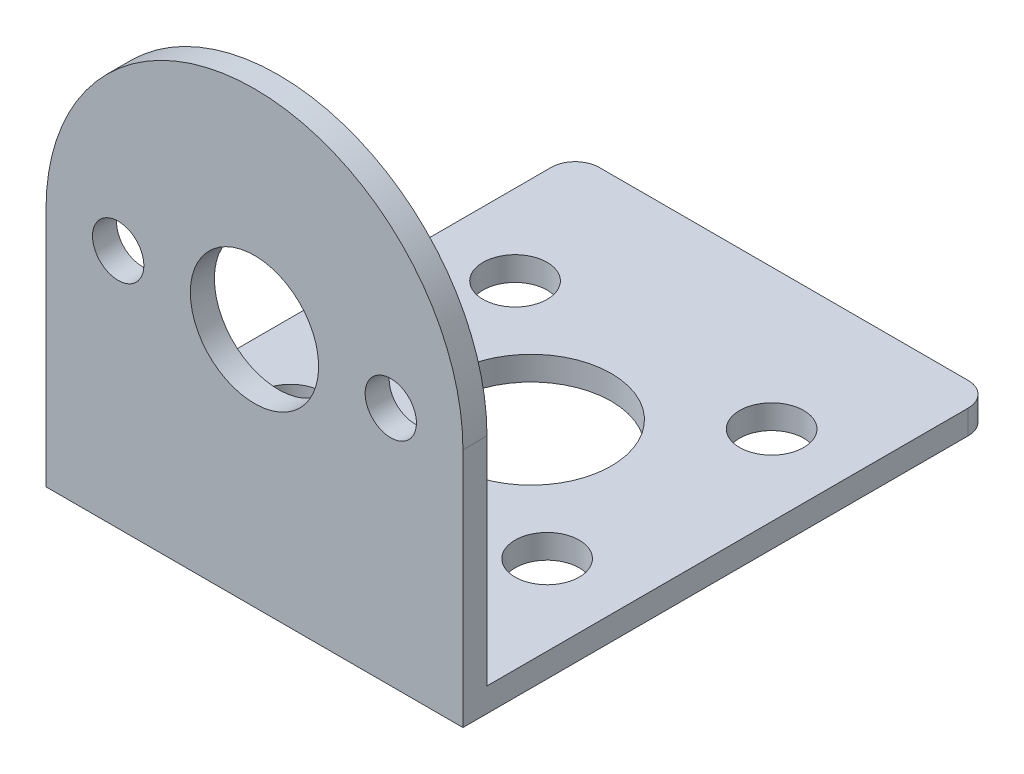
SolidWorks part; units mm, degrees
ref_plane "Front Plane" through (0, 0, 0) normal (0, 0, 1) x (1, 0, 0)
ref_plane "Top Plane" through (0, 0, 0) normal (0, 1, 0) x (1, 0, 0)
ref_plane "Right Plane" through (0, 0, 0) normal (1, 0, 0) x (0, 0, -1)
sketch "Sketch1" plane through (0, 0, 0) normal (0, 0, 1) x (1, 0, 0)
  line L1 (0, 0) -> (26, 0)
  line L2 (0, 0) -> (0, 15)
  line L4 (26, 0) -> (26, 15)
  arc A1 (26, 15) -> (0, 15) centre (13, 15) ccw
extrude "Boss-Extrude1" add sketch "Sketch1" along normal blind 1.5
sketch "Sketch2" plane through (0, 0, 0) normal (0, 0, -1) x (-1, 0, 0)
  circle A0 centre (-21.5, 15) radius 1.6
  circle A1 centre (-13, 15) radius 4
  circle A4 centre (-4.5, 15) radius 1.6
extrude "Cut-Extrude1" cut sketch "Sketch2" against normal through all
sketch "Sketch3" plane through (0, 0, 0) normal (0, 0, -1) x (-1, 0, 0)
  line L0 (0, 15) -> (0, 0) construction
  line L1 (-26, 0) -> (0, 0)
  line L2 (-26, 0) -> (-26, 1.5)
  line L3 (-26, 1.5) -> (0, 1.5)
  line L4 (0, 0) -> (0, 1.5)
extrude "Boss-Extrude4" add sketch "Sketch3" along normal blind 31.5
sketch "Sketch4" plane through (0, 0, 0) normal (0, -1, 0) x (1, 0, 0)
  circle A0 centre (13, -15.75) radius 5
  circle A1 centre (5, -8.75) radius 2
  circle A2 centre (21, -8.75) radius 2
  circle A3 centre (21, -22.75) radius 2
  circle A4 centre (5, -22.75) radius 2
extrude "Cut-Extrude2" cut sketch "Sketch4" against normal through all
fillet "Fillet1" radius 1.5 2 edges at (26, 0.75, -31.5) (0, 0.75, -31.5)
